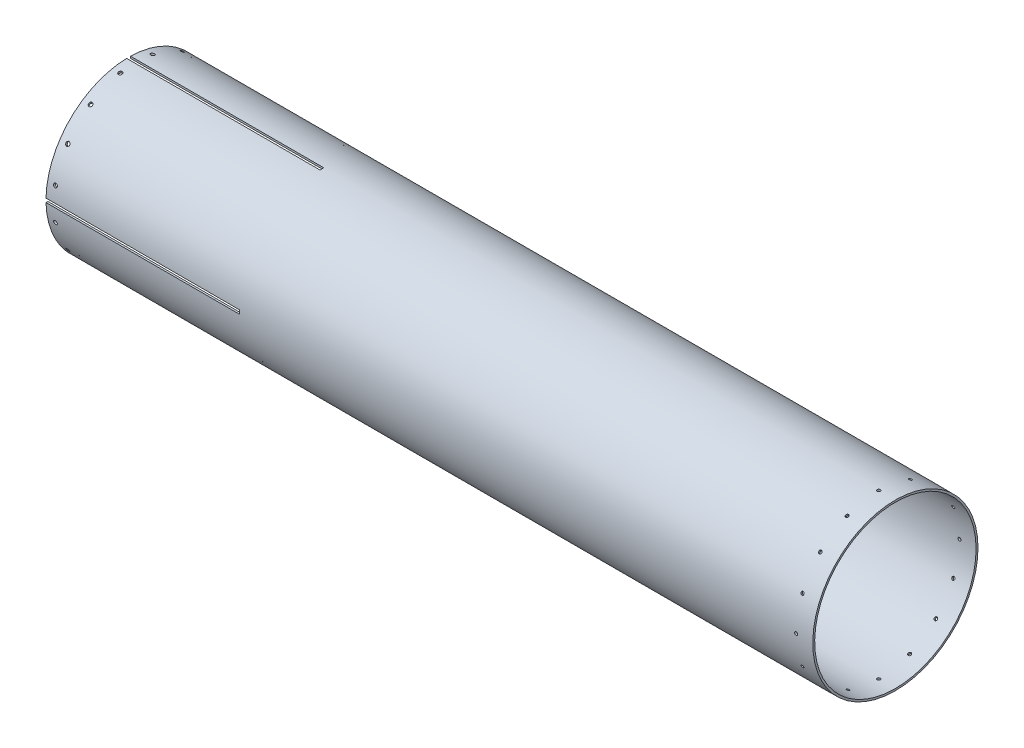
SolidWorks part; units mm, degrees
ref_plane "Płaszczyzna przednia" through (0, 0, 0) normal (0, 0, 1) x (1, 0, 0)
ref_plane "Płaszczyzna górna" through (0, 0, 0) normal (0, 1, 0) x (1, 0, 0)
ref_plane "Płaszczyzna prawa" through (0, 0, 0) normal (1, 0, 0) x (0, 0, -1)
sketch "Szkic1" plane through (0, 0, 0) normal (1, 0, 0) x (0, 0, -1)
  circle A0 centre (0, 0) radius 85
  circle A1 centre (0, 0) radius 87
  dimension "D1" = 170
  dimension "D2" = 174
extrude "Dodanie-wyciągnięcie1" add sketch "Szkic1" along normal blind 807.51
sketch "Szkic2" plane through (0, 0, 0) normal (1, 0, 0) x (0, 0, -1)
  line L0 (-129.3512, 0) -> (120.9381, 0) construction
  line L1 (0, 94.6472) -> (0, -98.8538) construction
  line L2 (-86.977, -2) -> (-2, -2)
  line L3 (-86.977, 2) -> (-2, 2)
  line L4 (-2, 86.977) -> (-2, 2)
  line L5 (2, 86.977) -> (2, 2)
  line L6 (-2, -2) -> (-2, -86.977)
  line L7 (2, 2) -> (86.977, 2)
  line L8 (-2, 94.6472) -> (-2, -98.8538) construction
  line L9 (2, -2) -> (86.977, -2)
  line L10 (-129.3512, 2) -> (120.9381, 2) construction
  line L11 (2, -2) -> (2, -86.977)
  line L12 (-129.3512, -2) -> (120.9381, -2) construction
  line L14 (2, 94.6472) -> (2, -98.8538) construction
  circle A0 centre (0, 0) radius 87 construction
  arc A1 (-86.977, 2) -> (-86.977, -2) centre (0, 0) ccw
  arc A2 (2, 86.977) -> (-2, 86.977) centre (0, 0) ccw
  arc A3 (86.977, -2) -> (86.977, 2) centre (0, 0) ccw
  arc A4 (-2, -86.977) -> (2, -86.977) centre (0, 0) ccw
  dimension "D1" = 2
  dimension "D2" = 2
  dimension "D3" = 2
  dimension "D4" = 2
extrude "Wytnij-wyciągnięcie1" cut sketch "Szkic2" along normal blind 203.6
sketch "Szkic3" plane through (0, 0, 0) normal (-1, 0, 0) x (0, 0, 1)
  line L0 (0, 100.995) -> (0, -98.9449) construction
  line L1 (0, 0) -> (16.9729, 85.3283) construction
  arc A0 (86.977, 2) -> (2, 86.977) centre (0, 0) ccw construction
  arc A1 (86.977, 2) -> (2, 86.977) centre (0, 0) ccw
  point P5 (0, 0)
  dimension "D1" = 11.25
sketch3d "Szkic 3D1" plane through (0, 0, 0) normal (0, 0, 1) x (1, 0, 0)
sketch3d "Szkic 3D2"
sketch "Szkic4" plane through (0, 85.3283, 16.9729) normal (0, 0.9808, 0.1951) x (1, 0, 0)
  line L0 (-15.3671, 0) -> (66.4096, 0) construction
  circle A0 centre (8.35, 0) radius 2
  dimension "D1" = 4
  dimension "D2" = 8.35
extrude "Wytnij-wyciągnięcie2" cut sketch "Szkic4" against normal blind 61.6
pattern_circular "Szyk kołowy1" count 16 over 360 about axis through (807.51, 0, 0) along (-1, 0, 0) of "Wytnij-wyciągnięcie2"
sketch "Szkic5" plane through (807.51, 0, 0) normal (1, 0, 0) x (0, 0, -1)
  line L0 (0, 100.995) -> (0, -98.9449) construction
  line L1 (0, 87) -> (0, -98.9449)
  circle A0 centre (0, 0) radius 87 construction
  circle A1 centre (0, 0) radius 87
sketch3d "Szkic 3D3"
sketch "Szkic6" plane through (0, 87, 0) normal (0, 1, 0) x (1, 0, 0)
  line L0 (807.51, -87) -> (807.51, 87) construction
  line L1 (746.8047, 0) -> (827.5661, 0) construction
  circle A0 centre (790.01, 0) radius 1.6
  dimension "D1" = 3.2
  dimension "D2" = 17.5
extrude "Wytnij-wyciągnięcie3" cut sketch "Szkic6" against normal blind 61.6
pattern_circular "Szyk kołowy3" count 16 over 360 about axis through (807.51, 0, 0) along (-1, 0, 0) of "Wytnij-wyciągnięcie3"
